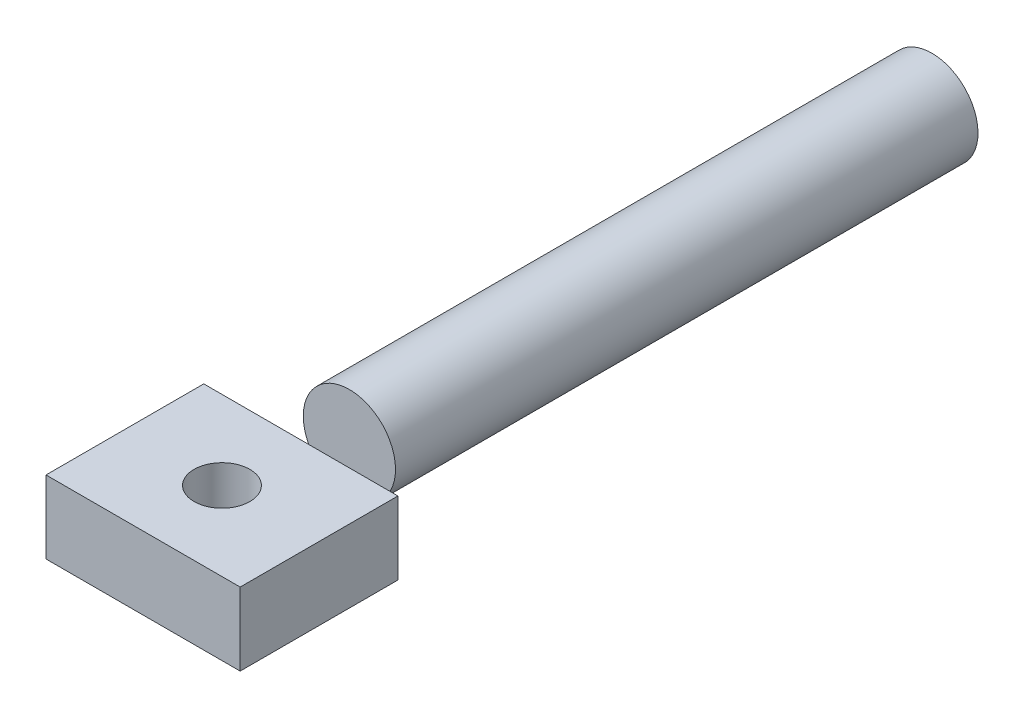
SolidWorks part; units mm, degrees
ref_plane "Plano frontal" through (0, 0, 0) normal (0, 0, 1) x (1, 0, 0)
ref_plane "Plano superior" through (0, 0, 0) normal (0, 1, 0) x (1, 0, 0)
ref_plane "Plano direito" through (0, 0, 0) normal (1, 0, 0) x (0, 0, -1)
sketch "Esboço1" plane through (0, 0, 0) normal (0, 1, 0) x (1, 0, 0)
  line L1 (-4, 3.25) -> (4, 3.25)
  line L2 (-4, 3.25) -> (-4, -3.25)
  line L3 (-4, -3.25) -> (4, -3.25)
  line L4 (4, 3.25) -> (4, -3.25)
  line L5 (-4, 3.25) -> (4, -3.25) construction
  line L6 (-4, -3.25) -> (4, 3.25) construction
  circle A0 centre (0, 0) radius 1.15
  point P0 (0, 0)
  dimension "D3" = 2.3
  dimension "D1" = 8
  dimension "D2" = 6.5
extrude "Ressalto-extrusão1" add sketch "Esboço1" along normal blind 3
sketch "Esboço2" plane through (0, 0, -3.25) normal (0, 0, -1) x (-1, 0, 0)
  line L0 (-2, 0) -> (2, 0)
  line L1 (-2, 0.816) -> (2, 0.816)
  line L2 (-2, 0.816) -> (-2, 0)
  line L4 (2, 0.816) -> (2, 0)
  line L5 (-2, 0.816) -> (0, 0) construction
  line L6 (0, 0) -> (2, 0.816) construction
  point P0 (0, 0)
  dimension "D1" = 4
extrude "Ressalto-extrusão2" add sketch "Esboço2" along normal blind 2
sketch "Esboço3" plane through (0, 0, -5.25) normal (0, 0, -1) x (-1, 0, 0)
  circle A0 centre (0, 1.9) radius 1.9
  dimension "D1" = 3.8
  dimension "D2" = 1.9
extrude "Ressalto-extrusão3" add sketch "Esboço3" along normal blind 24
